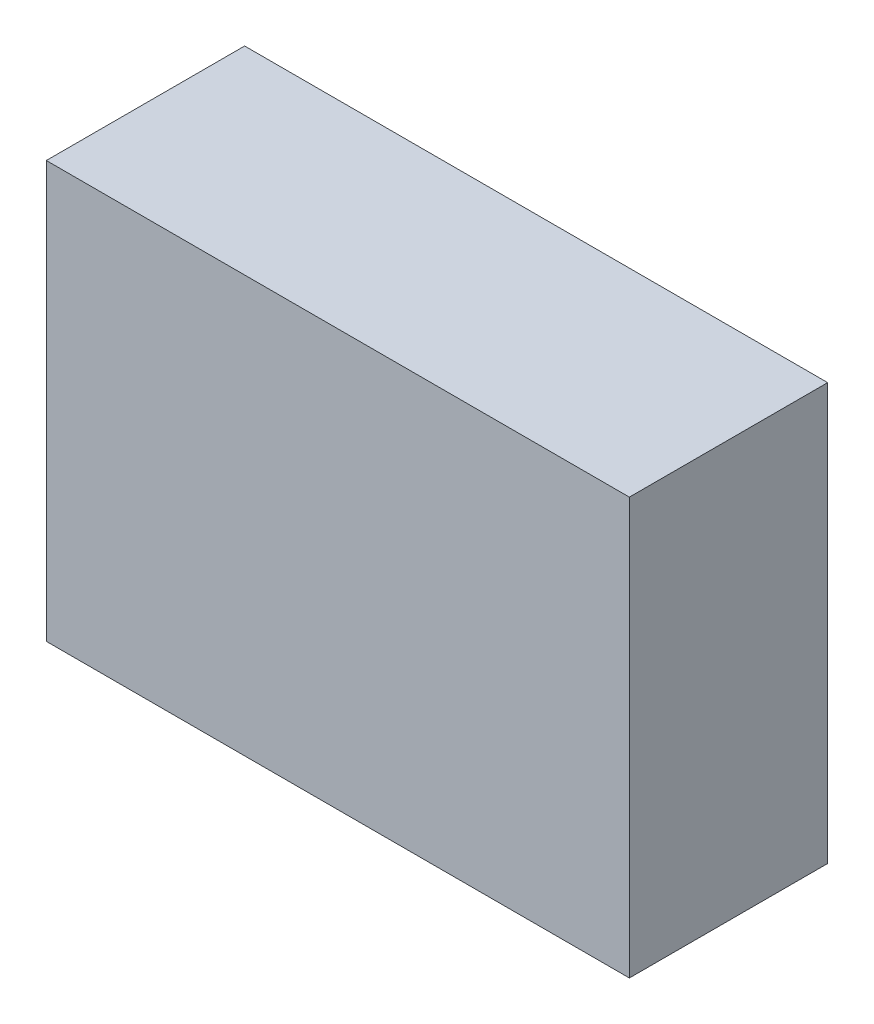
SolidWorks part; units mm, degrees
ref_plane "Front Plane" through (0, 0, 0) normal (0, 0, 1) x (1, 0, 0)
ref_plane "Top Plane" through (0, 0, 0) normal (0, 1, 0) x (1, 0, 0)
ref_plane "Right Plane" through (0, 0, 0) normal (1, 0, 0) x (0, 0, -1)
sketch "Sketch1" plane through (0, 0, 0) normal (0, 0, 1) x (1, 0, 0)
  line L1 (-136.6141, 103.4592) -> (10.3859, 103.4592)
  line L2 (-136.6141, 103.4592) -> (-136.6141, -1.5408)
  line L3 (-136.6141, -1.5408) -> (10.3859, -1.5408)
  line L4 (10.3859, 103.4592) -> (10.3859, -1.5408)
  line L5 (-136.6141, 103.4592) -> (10.3859, -1.5408) construction
  line L6 (-136.6141, -1.5408) -> (10.3859, 103.4592) construction
  point P0 (-63.1141, 50.9592)
  dimension "D1" = 147
  dimension "D2" = 105
extrude "Boss-Extrude1" add sketch "Sketch1" along normal blind 50
